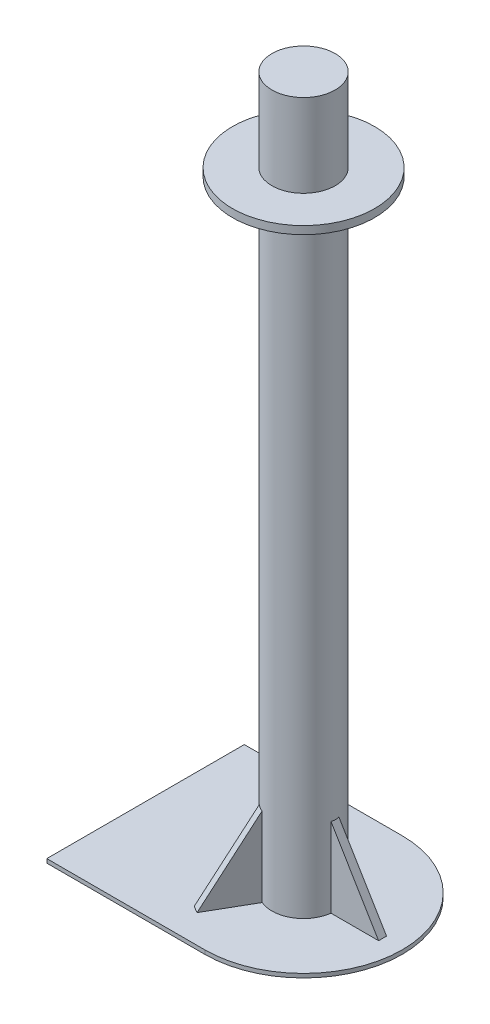
SolidWorks part; units mm, degrees
ref_plane "前视基准面" through (0, 0, 0) normal (0, 0, 1) x (1, 0, 0)
ref_plane "上视基准面" through (0, 0, 0) normal (0, 1, 0) x (1, 0, 0)
ref_plane "右视基准面" through (0, 0, 0) normal (1, 0, 0) x (0, 0, -1)
sketch "草图1" plane through (0, 0, 0) normal (0, 1, 0) x (1, 0, 0)
  line L0 (-198.4034, 0) -> (292.8798, 0) construction
  line L1 (-119.9142, -125) -> (-119.9142, 125)
  line L2 (-119.9142, 125) -> (80.0858, 125)
  line L3 (-119.9142, -125) -> (80.0858, -125)
  arc A0 (80.0858, 125) -> (80.0858, -125) centre (80.0858, 0) cw
  point P10 (-119.9142, 0)
  dimension "D1" = 250
  dimension "D3" = 125
  dimension "D2" = 200
extrude "凸台-拉伸1" add sketch "草图1" along normal blind 5
sketch "草图2" plane through (0, 5, 0) normal (0, 1, 0) x (1, 0, 0)
  circle A0 centre (80.0858, 0) radius 40
  dimension "D1" = 80
extrude "凸台-拉伸2" add sketch "草图2" along normal blind 900
ref_plane "基准面1" through (0, 790, 0) normal (0, -1, 0) x (-1, 0, 0)
sketch "草图3" plane through (0, 790, 0) normal (0, -1, 0) x (-1, 0, 0)
  circle A0 centre (-80.0858, 0) radius 90
  dimension "D1" = 180
extrude "凸台-拉伸3" add sketch "草图3" against normal blind 10
sketch "草图5" plane through (0, 0, 0) normal (0, 0, 1) x (1, 0, 0)
  line L0 (180.0858, 5) -> (108.3654, 5)
  line L1 (205.0858, 5) -> (80.0858, 5) construction
  line L2 (108.3654, 5) -> (108.3654, 124.5341)
  line L4 (108.3654, 124.5341) -> (180.0858, 5)
  line L5 (120.0858, 105) -> (120.0858, 5)
  line L6 (120.0858, 5) -> (120.0858, 790) construction
  dimension "D1" = 100
  dimension "D2" = 100
extrude "凸台-拉伸6" add sketch "草图5" along normal mid plane 10 contours L5 L4 L2 L0 | L4 L5 L0
pattern_circular "阵列(圆周)1" count 3 over 360 about axis through (80.0858, 0, 0) along (0, 1, 0) of "凸台-拉伸6"
